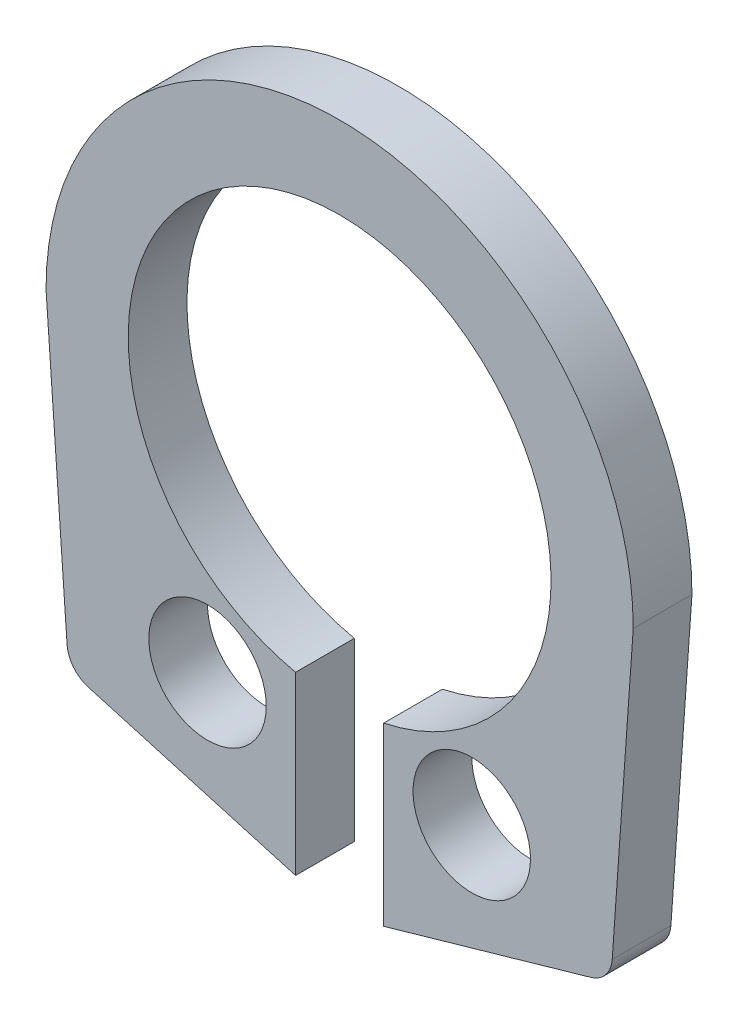
SolidWorks part; units mm, degrees
material "合金钢"
ref_plane "前视基准面" through (0, 0, 0) normal (0, 0, 1) x (1, 0, 0)
ref_plane "上视基准面" through (0, 0, 0) normal (0, 1, 0) x (1, 0, 0)
ref_plane "右视基准面" through (0, 0, 0) normal (1, 0, 0) x (0, 0, -1)
sketch "草图1" plane through (0, 0, 0) normal (0, 0, 1) x (1, 0, 0)
  line L2 (-0.75, -6.7114) -> (-0.75, -5.5209)
  line L3 (0, 7.0191) -> (0, -7.8021) construction
  line L7 (-5, -0.5775) -> (-4.6169, -5.9878)
  line L8 (-4.6169, -5.9878) -> (-0.75, -7.0958)
  line L9 (-0.75, -7.0958) -> (-0.75, -5.5209)
  line L10 (0.75, -6.7114) -> (0.75, -5.5209)
  line L11 (0.75, -7.0958) -> (0.75, -5.5209)
  line L12 (4.6169, -5.9878) -> (0.75, -7.0958)
  line L13 (5, -0.5775) -> (4.6169, -5.9878)
  line L14 (-0.75, -7.0958) -> (-0.75, -6.7114)
  line L15 (-0.75, -7.0958) -> (-0.75, -5.5209)
  line L16 (0.75, -7.0958) -> (0.75, -5.5209)
  line L17 (-0.75, -5.5209) -> (-0.75, -4.0985)
  line L18 (0.75, -5.5209) -> (0.75, -4.0985)
  arc A0 (-0.75, -5.5209) -> (0.75, -5.5209) centre (0, -0.5775) ccw
  circle A1 centre (0, -0.5775) radius 3.6
  arc A2 (5, -0.5775) -> (-5, -0.5775) centre (0, -0.5775) ccw
  circle A3 centre (-2.25, -4.852) radius 1
  circle A4 centre (2.25, -4.852) radius 1
  dimension "D1" = 5
  dimension "D2" = 3.6
  dimension "D4" = 1
  dimension "D3" = 0.75
  dimension "D5" = 1.5
extrude "凸台-拉伸1" add sketch "草图1" along normal blind 1 contours A2 L3 A1 A0 L10 L11 L12 L13 A4 | L3 A2 L7 L8 L9 L2 A0 A1 A3
fillet "圆角1" radius 0.5 2 edges at (4.6169, -5.9878, 0.5) (-4.6169, -5.9878, 0.5)
